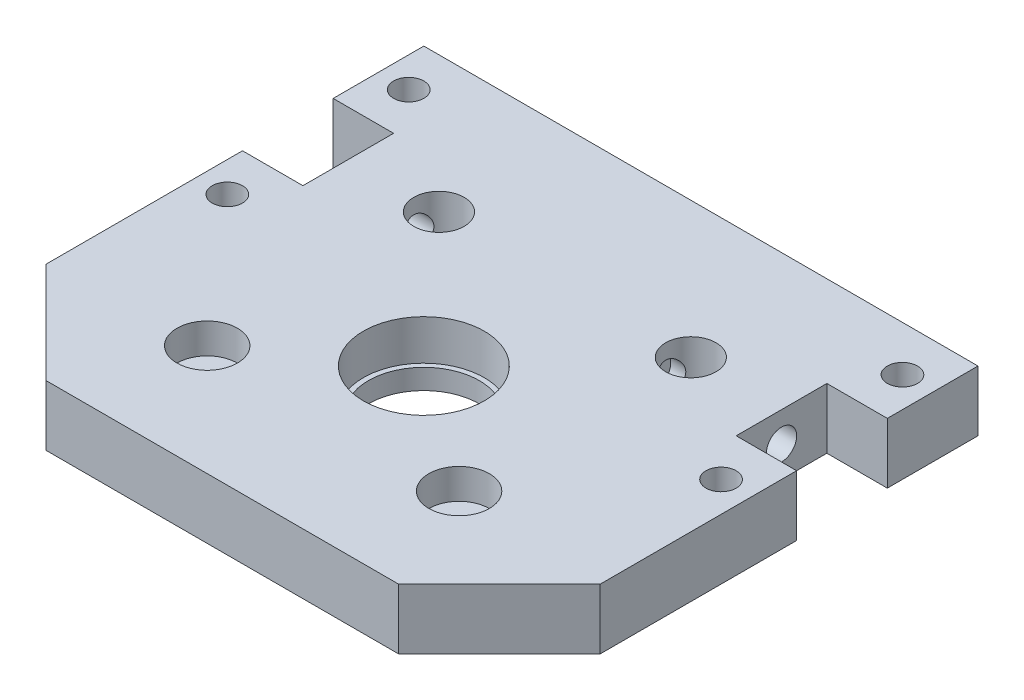
SolidWorks part; units mm, degrees
material "Beech"
ref_plane "Front Plane" through (0, 0, 0) normal (0, 0, 1) x (1, 0, 0)
ref_plane "Top Plane" through (0, 0, 0) normal (0, 1, 0) x (1, 0, 0)
ref_plane "Right Plane" through (0, 0, 0) normal (1, 0, 0) x (0, 0, -1)
sketch "Sketch1" plane through (0, 0, 0) normal (0, 1, 0) x (1, 0, 0)
  line L1 (-33, 25) -> (33, 25)
  line L2 (-33, 25) -> (-33, -70)
  line L3 (-33, -70) -> (33, -70)
  line L4 (33, 25) -> (33, -70)
  circle A0 centre (0, -30) radius 11
  dimension "D6" = 22
  dimension "D1" = 66
  dimension "D2" = 33
  dimension "D3" = 25
  dimension "D4" = 70
  dimension "D5" = 30
extrude "Boss-Extrude1" add sketch "Sketch1" along normal blind 12
sketch "Sketch3" plane through (0, 12, 0) normal (0, 1, 0) x (1, 0, 0)
  line L1 (55, 7) -> (43, 7)
  line L2 (33, 25) -> (33, -70)
  line L3 (43, 7) -> (43, -11)
  line L4 (43, -11) -> (55, -11)
  line L6 (33, -70) -> (55, -70)
  line L7 (55, -70) -> (55, -11)
  line L8 (33, 25) -> (55, 25)
  line L9 (55, 7) -> (55, 25)
  dimension "D1" = 12
  dimension "D2" = 18
  dimension "D3" = 18
  dimension "D4" = 22
extrude "Boss-Extrude3" add sketch "Sketch3" against normal blind 12
mirror "Mirror1" about plane through (0, 0, 0) normal (1, 0, 0) of "Boss-Extrude3"
sketch "Sketch4" plane through (0, 12, 0) normal (0, 1, 0) x (1, 0, 0)
  circle A0 centre (0, -30) radius 12
  dimension "D1" = 24
extrude "Cut-Extrude1" cut sketch "Sketch4" against normal blind 8
sketch "Sketch6" plane through (0, 12, 0) normal (0, 1, 0) x (1, 0, 0)
  line L0 (-63.5336, -48) -> (64.8117, -48) construction
  circle A0 centre (0, -30) radius 12 construction
  circle A1 centre (-25, -48) radius 6
  circle A2 centre (25, -48) radius 6
  dimension "D2" = 25
  dimension "D3" = 25
  dimension "D4" = 12
  dimension "D5" = 12
  dimension "D1" = 18
extrude "Cut-Extrude2" cut sketch "Sketch6" against normal blind 6
chamfer "Chamfer1" distance 20 angle 45 2 edges at (55, 6, 70) (-55, 6, 70)
sketch "Sketch7" plane through (0, 12, 0) normal (0, 1, 0) x (1, 0, 0)
  line L0 (-49, 22.071) -> (-49, -31.0852) construction
  line L1 (-59.9918, 16) -> (-35.4854, 16) construction
  line L2 (-63.8876, -20) -> (-39.0752, -20) construction
  line L3 (-55, -11) -> (-43, -11) construction
  line L4 (-42.1899, -2) -> (-20.2042, -2) construction
  line L6 (-43, -11) -> (-43, 7) construction
  circle A0 centre (-49, 16) radius 3
  circle A1 centre (-49, -20) radius 3
  circle A2 centre (-25, -2) radius 5
  dimension "D2" = 6
  dimension "D3" = 6
  dimension "D4" = 18
  dimension "D5" = 10
  dimension "D1" = 9
extrude "Cut-Extrude3" cut sketch "Sketch7" against normal up to next
sketch "Sketch9" plane through (-43, 0, 0) normal (-1, 0, 0) x (0, 0, 1)
  line L0 (11, 12) -> (-7, 12) construction
  line L1 (-7, 0) -> (-7, 12) construction
  circle A0 centre (2, 6) radius 3
  dimension "D1" = 6
  dimension "D2" = 6
  dimension "D3" = 9
extrude "Cut-Extrude5" cut sketch "Sketch9" against normal blind 25
mirror "Mirror2" about plane through (0, 0, 0) normal (1, 0, 0) of "Cut-Extrude5", "Cut-Extrude3"
